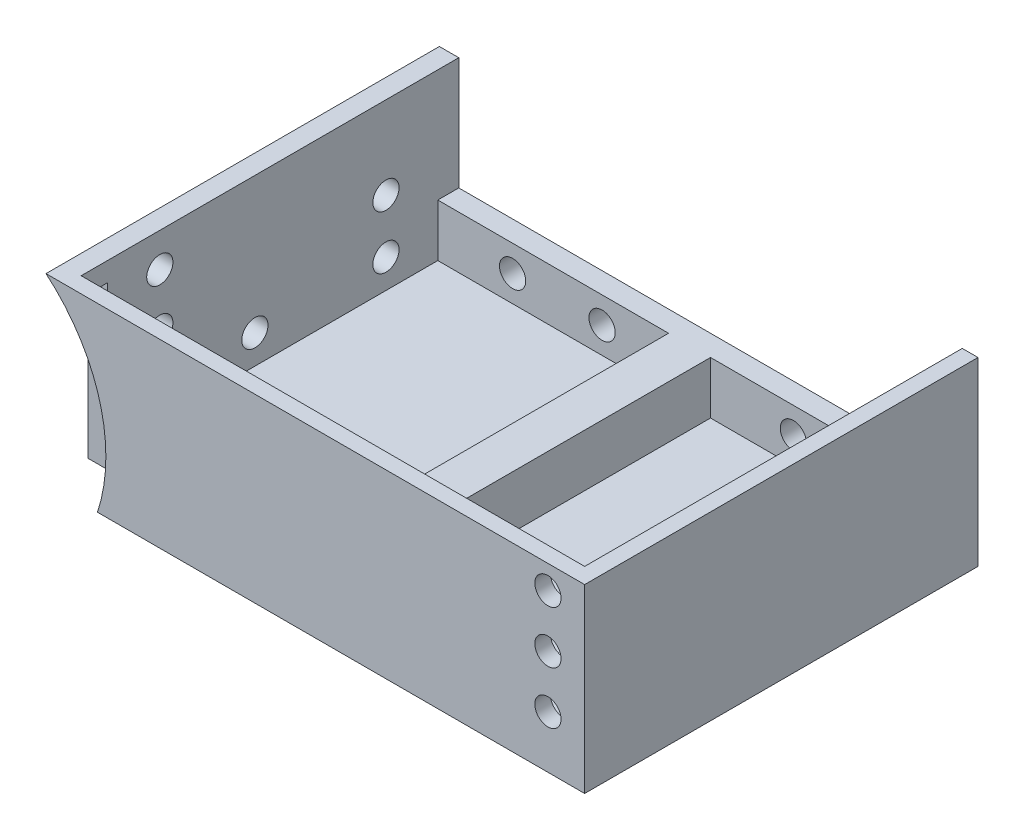
SolidWorks part; units mm, degrees
ref_plane "Plan de face" through (0, 0, 0) normal (0, 0, 1) x (1, 0, 0)
ref_plane "Plan de dessus" through (0, 0, 0) normal (0, 1, 0) x (1, 0, 0)
ref_plane "Plan de droite" through (0, 0, 0) normal (1, 0, 0) x (0, 0, -1)
sketch "Cube" plane through (0, 0, 0) normal (0, 1, 0) x (1, 0, 0)
  line L1 (-109.2105, 63.4868) -> (40.7895, 63.4868)
  line L2 (-109.2105, 63.4868) -> (-109.2105, -86.5132)
  line L3 (-109.2105, -86.5132) -> (40.7895, -86.5132)
  line L4 (40.7895, 63.4868) -> (40.7895, -86.5132)
  dimension "D1" = 150
  dimension "D2" = 150
extrude "Boss.-Extru.1" add sketch "Cube" along normal blind 34.5
sketch "Pave" plane through (0, 34.5, 0) normal (0, 1, 0) x (1, 0, 0)
  line L0 (40.7895, -86.5132) -> (40.7895, 63.4868) construction
  line L1 (-109.2105, -86.5132) -> (40.7895, -86.5132) construction
  line L2 (40.7895, 63.4868) -> (-109.2105, 63.4868) construction
  line L4 (37.7895, -83.5132) -> (-58.2105, -83.5132)
  line L5 (37.7895, -83.5132) -> (37.7895, 60.4868)
  line L6 (37.7895, 60.4868) -> (-58.2105, 60.4868)
  line L7 (-58.2105, -83.5132) -> (-58.2105, 60.4868)
  point P0 (37.7895, -83.5132)
  point P5 (-58.2105, 60.4868)
  dimension "D1" = 3
  dimension "D2" = 3
  dimension "D3" = 3
  dimension "D4" = 99
extrude "Enlèv. mat.-Extru.1" cut sketch "Pave" against normal blind 31.5
sketch "Vis1" plane through (0, 0, 86.5132) normal (0, 0, 1) x (1, 0, 0)
  line L0 (40.7895, 34.5) -> (40.7895, 0) construction
  line L1 (-109.2105, 0) -> (40.7895, 0) construction
  circle A0 centre (33.7895, 10) radius 2.5
  circle A1 centre (33.7895, 20) radius 2.5
  circle A2 centre (33.7895, 30) radius 2.5
  point P0 (33.7895, 10)
  point P3 (33.7895, 20)
  point P4 (33.7895, 30)
  dimension "D1" = 7
  dimension "D2" = 7
  dimension "D3" = 7
  dimension "D4" = 10
  dimension "D5" = 20
  dimension "D6" = 30
extrude "Enlèv. mat.-Extru.2" cut sketch "Vis1" against normal blind 5
sketch "Vis2" plane through (0, 0, -63.4868) normal (0, 0, -1) x (-1, 0, 0)
  line L0 (-40.7895, 34.5) -> (-40.7895, 0) construction
  line L1 (-40.7895, 0) -> (109.2105, 0) construction
  circle A0 centre (-33.7895, 10) radius 2.5
  circle A1 centre (-33.7895, 20) radius 2.5
  circle A2 centre (-33.7895, 30) radius 2.5
  point P0 (-33.7895, 10)
  point P1 (-33.7895, 20)
  point P2 (-33.7895, 30)
  dimension "D1" = 7
  dimension "D2" = 7
  dimension "D3" = 7
  dimension "D4" = 10
  dimension "D5" = 20
  dimension "D6" = 30
extrude "Enlèv. mat.-Extru.3" cut sketch "Vis2" against normal blind 5
sketch "Pave proche moteur" plane through (0, 34.5, 0) normal (0, 1, 0) x (1, 0, 0)
  line L0 (-109.2105, -86.5132) -> (40.7895, -86.5132) construction
  line L1 (-58.2105, 60.4868) -> (-58.2105, -83.5132) construction
  line L2 (40.7895, 63.4868) -> (-109.2105, 63.4868) construction
  line L4 (-61.2105, 50.4868) -> (-73.7105, 50.4868)
  line L5 (-61.2105, 50.4868) -> (-61.2105, -73.5132)
  line L6 (-61.2105, -73.5132) -> (-73.7105, -73.5132)
  line L7 (-73.7105, 50.4868) -> (-73.7105, -73.5132)
  point P0 (-61.2105, -73.5132)
  point P5 (-61.2105, 50.4868)
  dimension "D1" = 13
  dimension "D2" = 3
  dimension "D3" = 13
  dimension "D4" = 3
  dimension "D5" = 12.5
extrude "Enlèv. mat.-Extru.4" cut sketch "Pave proche moteur" against normal blind 31.5
sketch "Pave Roue libre" plane through (0, 34.5, 0) normal (0, 1, 0) x (1, 0, 0)
  line L0 (40.7895, 63.4868) -> (-109.2105, 63.4868) construction
  line L1 (-58.2105, 60.4868) -> (-58.2105, -83.5132) construction
  line L2 (-109.2105, -86.5132) -> (40.7895, -86.5132) construction
  line L3 (-71.5505, 53.4868) -> (-104.4105, 53.4868)
  line L4 (-71.5505, 53.4868) -> (-71.5505, 69.1835)
  line L5 (-71.5505, 69.1835) -> (-104.4105, 69.1835)
  line L6 (-104.4105, 53.4868) -> (-104.4105, 69.1835)
  line L8 (-71.5505, -76.5132) -> (-104.4105, -76.5132)
  line L9 (-71.5505, -76.5132) -> (-71.5505, -94.9327)
  line L10 (-71.5505, -94.9327) -> (-104.4105, -94.9327)
  line L11 (-104.4105, -76.5132) -> (-104.4105, -94.9327)
  point P0 (-71.5505, 53.4868)
  point P9 (-71.5505, -76.5132)
  dimension "D1" = 10
  dimension "D2" = 13.34
  dimension "D3" = 32.86
  dimension "D4" = 13.34
  dimension "D5" = 10
extrude "Enlèv. mat.-Extru.5" cut sketch "Pave Roue libre" against normal blind 36
sketch "Cables" plane through (0, 34.5, 0) normal (0, 1, 0) x (1, 0, 0)
  line L0 (40.7895, 63.4868) -> (-71.5505, 63.4868) construction
  line L1 (-58.2105, 60.4868) -> (-58.2105, -83.5132) construction
  line L2 (-71.5505, -86.5132) -> (40.7895, -86.5132) construction
  line L3 (-58.2105, 60.4868) -> (-58.2105, -83.5132) construction
  line L5 (-100.8905, -5.5132) -> (-78.5305, -5.5132)
  line L6 (-100.8905, -5.5132) -> (-100.8905, 4.4868)
  line L7 (-100.8905, 4.4868) -> (-78.5305, 4.4868)
  line L8 (-78.5305, -5.5132) -> (-78.5305, 4.4868)
  line L9 (-100.8905, -17.5132) -> (-78.5305, -17.5132)
  line L10 (-100.8905, -17.5132) -> (-100.8905, -27.5132)
  line L11 (-100.8905, -27.5132) -> (-78.5305, -27.5132)
  line L12 (-78.5305, -17.5132) -> (-78.5305, -27.5132)
  point P0 (-100.8905, -5.5132)
  point P5 (-100.8905, -17.5132)
  dimension "D1" = 69
  dimension "D2" = 42.68
  dimension "D3" = 69
  dimension "D4" = 42.68
  dimension "D5" = 22.36
  dimension "D6" = 10
  dimension "D7" = 22.36
  dimension "D8" = 10
extrude "Enlèv. mat.-Extru.6" cut sketch "Cables" against normal blind 36
sketch "Roue ext" plane through (0, 0, 86.5132) normal (0, 0, 1) x (1, 0, 0)
  circle A0 centre (-82.5, 10) radius 32
  point P0 (-82.5, 10)
extrude "Enlèv. mat.-Extru.7" cut sketch "Roue ext" against normal blind 8
sketch "Roue inter" plane through (0, 0, 86.5132) normal (0, 0, 1) x (1, 0, 0)
  circle A0 centre (-82.5, 10) radius 16.02
  point P0 (-82.5, 10)
extrude "Enlèv. mat.-Extru.8" cut sketch "Roue inter" against normal blind 69
sketch "Roue ext2" plane through (0, 0, -63.4868) normal (0, 0, -1) x (-1, 0, 0)
  circle A0 centre (82.5, 10) radius 32
  point P0 (82.5, 10)
extrude "Enlèv. mat.-Extru.9" cut sketch "Roue ext2" against normal blind 7.5
sketch "Roue inter2" plane through (0, 0, -63.4868) normal (0, 0, -1) x (-1, 0, 0)
  circle A0 centre (82.5, 10) radius 16.02
  point P0 (82.5, 10)
extrude "Enlèv. mat.-Extru.10" cut sketch "Roue inter2" against normal blind 69
sketch "Vis Moteur pour support" plane through (-58.2105, 0, 0) normal (1, 0, 0) x (0, 0, -1)
  line L0 (55.9868, 3) -> (-78.5132, 3) construction
  line L1 (-78.5132, 3) -> (-78.5132, 30.8332) construction
  line L2 (55.9868, 30.8332) -> (55.9868, 3) construction
  circle A0 centre (-68.5132, 8) radius 2.5
  circle A1 centre (-68.5132, 18) radius 2.5
  circle A2 centre (-68.5132, 28) radius 2.5
  circle A3 centre (45.9868, 8) radius 2.5
  circle A4 centre (45.9868, 18) radius 2.5
  circle A5 centre (45.9868, 28) radius 2.5
  point P0 (-68.5132, 8)
  point P1 (-68.5132, 18)
  point P2 (-68.5132, 28)
  point P13 (45.9868, 18)
  point P14 (45.9868, 28)
  point P15 (45.9868, 8)
  dimension "D7" = 5
  dimension "D1" = 5
  dimension "D2" = 15
  dimension "D3" = 25
  dimension "D4" = 10
  dimension "D5" = 10
  dimension "D6" = 10
  dimension "D8" = 15
  dimension "D9" = 25
  dimension "D10" = 10
  dimension "D11" = 10
  dimension "D12" = 10
extrude "Enlèv. mat.-Extru.11" cut sketch "Vis Moteur pour support" against normal blind 10
sketch "Esquisse1" plane through (0, 3, 0) normal (0, 1, 0) x (1, 0, 0)
  line L0 (-58.2105, 55.9868) -> (-58.2105, -78.5132) construction
  line L1 (37.7895, 60.4868) -> (-51.275, 60.4868) construction
  line L2 (37.7895, -83.5132) -> (37.7895, 60.4868) construction
  line L3 (-58.2105, -15.5132) -> (-14.2105, -15.5132)
  line L4 (-58.2105, -15.5132) -> (-58.2105, -7.5132)
  line L5 (-58.2105, -7.5132) -> (-14.2105, -7.5132)
  line L6 (37.7895, -15.5132) -> (37.7895, -7.5132)
  line L7 (-51.275, -83.5132) -> (37.7895, -83.5132) construction
  line L8 (-14.2105, 60.4868) -> (-6.2105, 60.4868)
  line L9 (-14.2105, 60.4868) -> (-14.2105, -7.5132)
  line L10 (-14.2105, -83.5132) -> (-6.2105, -83.5132)
  line L11 (-6.2105, 60.4868) -> (-6.2105, -7.5132)
  line L12 (-14.2105, -15.5132) -> (-14.2105, -83.5132)
  line L13 (-6.2105, -15.5132) -> (37.7895, -15.5132)
  line L14 (-6.2105, -15.5132) -> (-6.2105, -83.5132)
  line L15 (-6.2105, -7.5132) -> (37.7895, -7.5132)
  point P0 (-58.2105, -11.5132)
  point P5 (-58.2105, -7.5132)
  point P6 (-58.2105, -15.5132)
  point P13 (-10.2105, 60.4868)
  point P14 (-14.2105, 60.4868)
  point P15 (-6.2105, 60.4868)
  dimension "D1" = 72
  dimension "D2" = 68
  dimension "D3" = 76
  dimension "D4" = 48
  dimension "D5" = 52
  dimension "D6" = 44
extrude "Boss.-Extru.2" add sketch "Esquisse1" along normal blind 10
sketch "Esquisse2" plane through (0, 0, 15.5132) normal (0, 0, 1) x (1, 0, 0)
  line L0 (-58.2105, 3) -> (-14.2105, 3) construction
  line L1 (-6.2105, 3) -> (37.7895, 3) construction
  circle A0 centre (-43.9429, 8) radius 2.5
  circle A1 centre (-26.8896, 8) radius 2.5
  circle A2 centre (9.5885, 8) radius 2.5
  circle A3 centre (23.5624, 8) radius 2.5
  point P0 (-43.9429, 8)
  point P1 (-26.8896, 8)
  point P4 (9.5885, 8)
  point P5 (23.5624, 8)
  dimension "D1" = 5
  dimension "D2" = 5
  dimension "D3" = 5
extrude "Enlèv. mat.-Extru.12" cut sketch "Esquisse2" against normal blind 10
sketch "Esquisse3" plane through (0, 3, 0) normal (0, 1, 0) x (1, 0, 0)
  line L0 (-68.0903, -73.5132) -> (-61.2105, -73.5132) construction
  line L1 (-61.2105, 50.4868) -> (-64.6504, 50.4868)
  line L2 (-61.2105, 50.4868) -> (-61.2105, -73.5132)
  line L3 (-61.2105, -73.5132) -> (-64.6504, -73.5132)
  line L4 (-64.6504, 50.4868) -> (-64.6504, -73.5132)
extrude "Boss.-Extru.3" add sketch "Esquisse3" along normal blind 31
sketch "Esquisse5" plane through (0, 34, 0) normal (0, 1, 0) x (1, 0, 0)
  line L1 (-61.2105, 50.4868) -> (-64.6504, 50.4868)
  line L2 (-61.2105, 50.4868) -> (-61.2105, -73.5132)
  line L3 (-61.2105, -73.5132) -> (-64.6504, -73.5132)
  line L4 (-64.6504, 50.4868) -> (-64.6504, -73.5132)
extrude "Boss.-Extru.4" add sketch "Esquisse5" along normal blind 0.5
sketch "Esquisse6" plane through (-58.2105, 0, 0) normal (1, 0, 0) x (0, 0, -1)
  circle A0 centre (-68.5132, 28) radius 2.5
  circle A1 centre (-68.5132, 18) radius 2.5
  circle A2 centre (-68.5132, 8) radius 2.5
  circle A3 centre (45.9868, 28) radius 2.5
  circle A4 centre (45.9868, 18) radius 2.5
  circle A5 centre (45.9868, 8) radius 2.5
extrude "Enlèv. mat.-Extru.13" cut sketch "Esquisse6" against normal blind 10
sketch "Esquisse7" plane through (-58.2105, 0, 0) normal (1, 0, 0) x (0, 0, -1)
  circle A0 centre (0, 8.5279) radius 2.5
  circle A2 centre (0, 18.7509) radius 2.5
  circle A3 centre (-25.4002, 8.5279) radius 2.5
  circle A4 centre (-25.4002, 18.7509) radius 2.5
  circle A5 centre (-50.3865, 8.5279) radius 2.5
  circle A6 centre (23.6295, 8.5279) radius 2.5
extrude "Enlèv. mat.-Extru.14" cut sketch "Esquisse7" against normal blind 10
sketch "Esquisse8" plane through (0, 3, 0) normal (0, 1, 0) x (1, 0, 0)
  line L0 (37.7895, -83.5132) -> (37.7895, -15.5132) construction
  line L1 (-58.2105, -83.5132) -> (37.7895, -83.5132) construction
  line L2 (37.7895, 60.4868) -> (-6.2105, 60.4868) construction
  circle A0 centre (19.7895, -43.5132) radius 2.5
  circle A1 centre (19.7895, 20.4868) radius 2.5
  point P0 (19.7895, -43.5132)
  point P7 (19.7895, 20.4868)
  dimension "D3" = 40
  dimension "D1" = 18
  dimension "D2" = 40
extrude "Enlèv. mat.-Extru.15" cut sketch "Esquisse8" against normal blind 10
sketch "Esquisse9" plane through (0, 34.5, 0) normal (0, 1, 0) x (1, 0, 0)
  line L1 (-61.9148, -86.5132) -> (-109.2105, -86.5132)
  line L2 (-61.9148, -86.5132) -> (-61.9148, -11.5132)
  line L3 (-61.9148, 63.4868) -> (-109.2105, 63.4868)
  line L4 (-109.2105, -86.5132) -> (-109.2105, 63.4868)
  line L5 (-61.9148, -11.5132) -> (40.7895, -11.5132)
  line L7 (-61.9148, 63.4868) -> (40.7895, 63.4868)
  line L8 (40.7895, -11.5132) -> (40.7895, 63.4868)
extrude "Enlèv. mat.-Extru.17" cut sketch "Esquisse9" against normal blind 40
